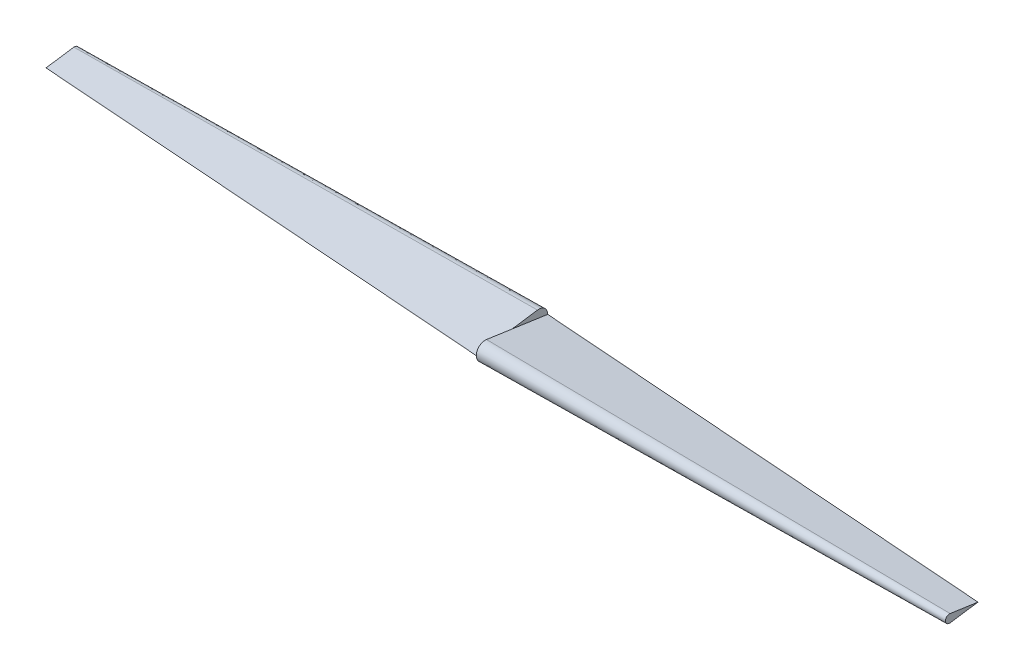
SolidWorks part; units mm, degrees
ref_plane "Front Plane" through (0, 0, 0) normal (0, 0, 1) x (1, 0, 0)
ref_plane "Top Plane" through (0, 0, 0) normal (0, 1, 0) x (1, 0, 0)
ref_plane "Right Plane" through (0, 0, 0) normal (1, 0, 0) x (0, 0, -1)
sketch "Sketch1" plane through (0, 0, 0) normal (1, 0, 0) x (0, 0, -1)
  line L0 (-50.8, 0) -> (50.8, 0) construction
  line L1 (0, 0) -> (0, 17.6962) construction
  line L2 (50.8, 0) -> (-36.2857, 12.5697)
  line L3 (50.8, 0) -> (-36.2857, -12.5697)
  arc A0 (-36.2857, 12.5697) -> (-36.2857, -12.5697) centre (-38.1, 0) ccw
  dimension "D2" = 12.7
  dimension "D1" = 101.6
extrude "Boss-Extrude1" add sketch "Sketch1" along normal blind 660.4 draft 0.6
sketch "Sketch2" plane through (0, 0, 0) normal (1, 0, 0) x (0, 0, -1)
  line L0 (0, 0) -> (0, 24.4736) construction
pattern_circular "CirPattern1" count 2 every 180 about axis through (0, 0, 0) along (0, 1, 0) of "Boss-Extrude1"
